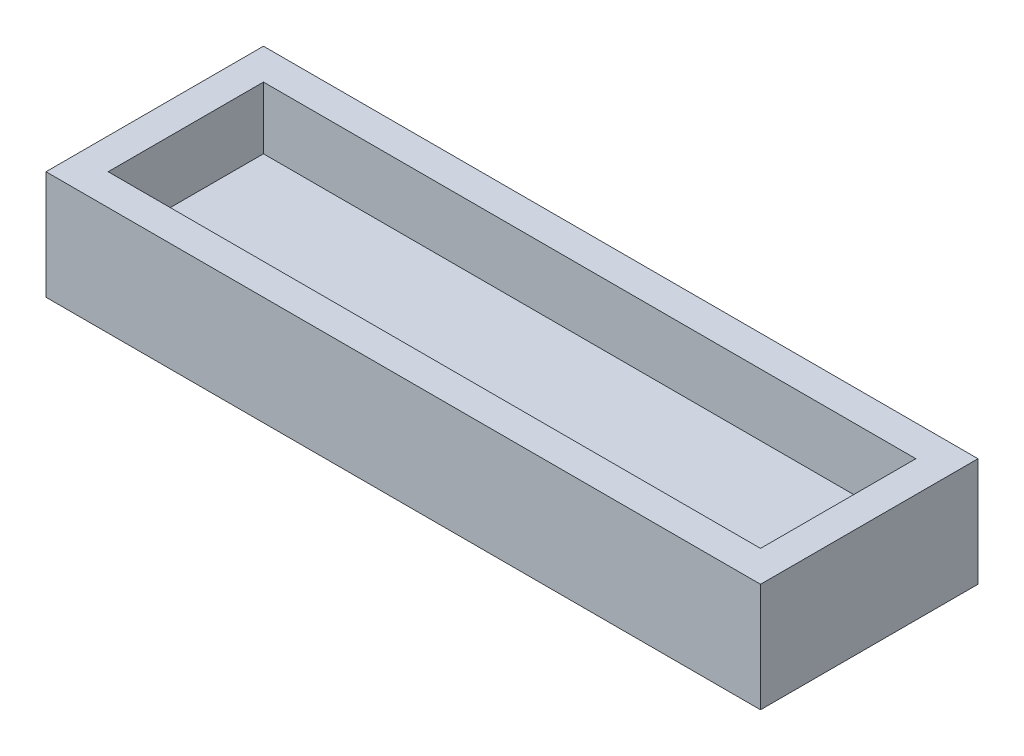
SolidWorks part; units mm, degrees
ref_plane "Front Plane" through (0, 0, 0) normal (0, 0, 1) x (1, 0, 0)
ref_plane "Top Plane" through (0, 0, 0) normal (0, 1, 0) x (1, 0, 0)
ref_plane "Right Plane" through (0, 0, 0) normal (1, 0, 0) x (0, 0, -1)
sketch "Sketch1" plane through (0, 0, 0) normal (0, 1, 0) x (1, 0, 0)
  line L1 (-21, 5) -> (21, 5)
  line L2 (-21, 5) -> (-21, -5)
  line L3 (-21, -5) -> (21, -5)
  line L4 (21, 5) -> (21, -5)
  line L5 (-21, 5) -> (21, -5) construction
  line L6 (-21, -5) -> (21, 5) construction
  point P0 (0, 0)
extrude "Boss-Extrude1" add sketch "Sketch1" along normal blind 3
sketch "Sketch2" plane through (0, 0, 0) normal (0, -1, 0) x (1, 0, 0)
  line L0 (-21, -5) -> (-21, 5) construction
  line L1 (21, -5) -> (-21, -5)
  line L2 (21, -5) -> (21, 5)
  line L3 (21, 5) -> (-21, 5)
  line L4 (-21, -5) -> (-21, 5)
  line L9 (23, -7) -> (23, 7)
  line L14 (23, 7) -> (-23, 7)
  line L15 (-23, -7) -> (-23, 7)
  line L16 (23, -7) -> (-23, -7)
  dimension "D2" = 2
extrude "Boss-Extrude2" add sketch "Sketch2" against normal offset from surface (7 mm away) 4 up to face at (0, 3, 0) offset beyond the face yes
